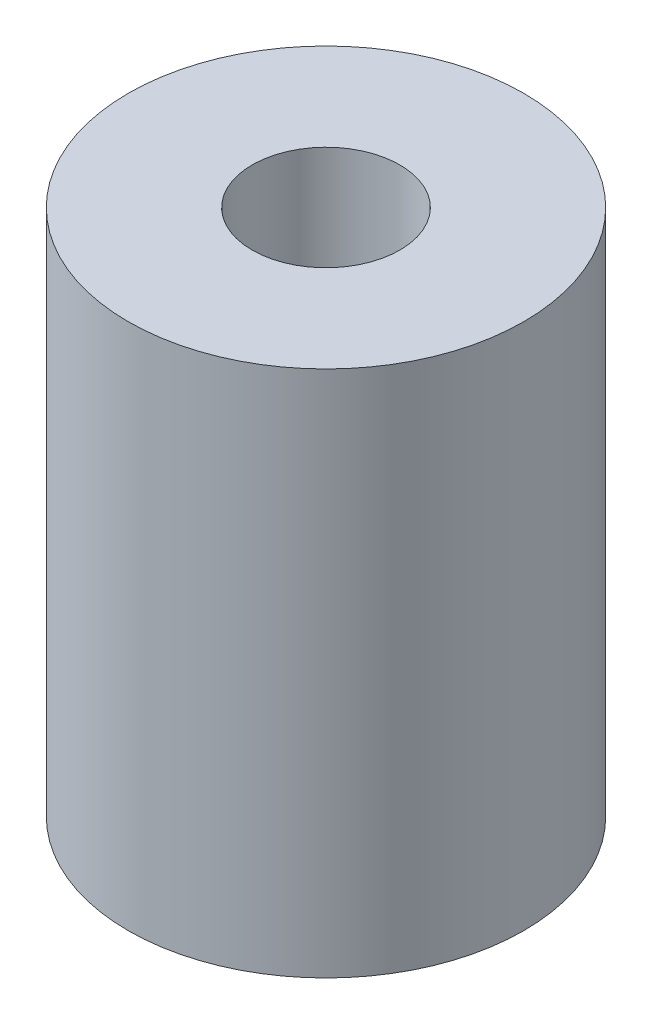
SolidWorks part; units mm, degrees
material "ABS"
ref_plane "Front Plane" through (0, 0, 0) normal (0, 0, 1) x (1, 0, 0)
ref_plane "Top Plane" through (0, 0, 0) normal (0, 1, 0) x (1, 0, 0)
ref_plane "Right Plane" through (0, 0, 0) normal (1, 0, 0) x (0, 0, -1)
sketch "Sketch1" plane through (0, 0, 0) normal (0, 1, 0) x (1, 0, 0)
  circle A0 centre (0, 0) radius 2.8
  circle A1 centre (0, 0) radius 7.5
  dimension "D1" = 5.6
  dimension "D2" = 15
extrude "Boss-Extrude1" add sketch "Sketch1" along normal blind 20 contours A1
